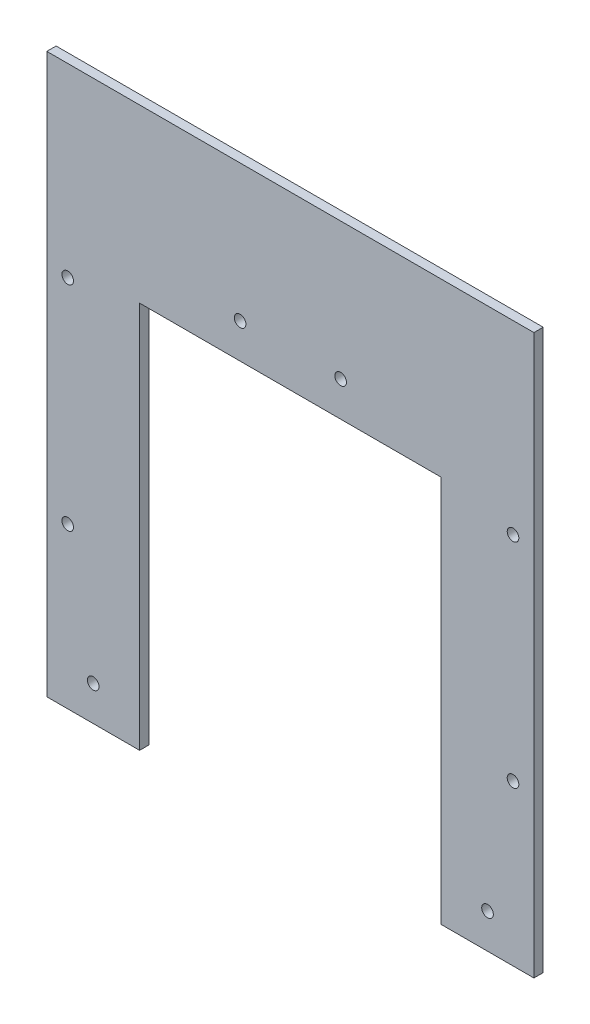
SolidWorks part; units mm, degrees
ref_plane "Alzado" through (0, 0, 0) normal (0, 0, 1) x (1, 0, 0)
ref_plane "Planta" through (0, 0, 0) normal (0, 1, 0) x (1, 0, 0)
ref_plane "Vista lateral" through (0, 0, 0) normal (1, 0, 0) x (0, 0, -1)
sketch "Croquis1" plane through (0, 0, 0) normal (0, 0, 1) x (1, 0, 0)
  line L0 (70, 0) -> (70, 167)
  line L1 (-100, 0) -> (-60, 0)
  line L2 (-100, 0) -> (-100, 241)
  line L3 (-100, 241) -> (110, 241)
  line L4 (110, 0) -> (110, 241)
  line L5 (70, 167) -> (-60, 167)
  line L6 (-60, 167) -> (-60, 0)
  line L7 (70, 0) -> (110, 0)
  circle A0 centre (-80, 15) radius 2.5
  circle A1 centre (-91, 69.01) radius 2.5
  circle A2 centre (-91, 161.01) radius 2.5
  circle A3 centre (-16.6667, 182) radius 2.5
  circle A4 centre (26.6667, 182) radius 2.5
  circle A5 centre (101, 161.01) radius 2.5
  circle A6 centre (101, 69.01) radius 2.5
  circle A7 centre (90, 15) radius 2.5
  dimension "D1" = 241
  dimension "D2" = 210
extrude "Saliente-Extruir1" add sketch "Croquis1" along normal blind 4
